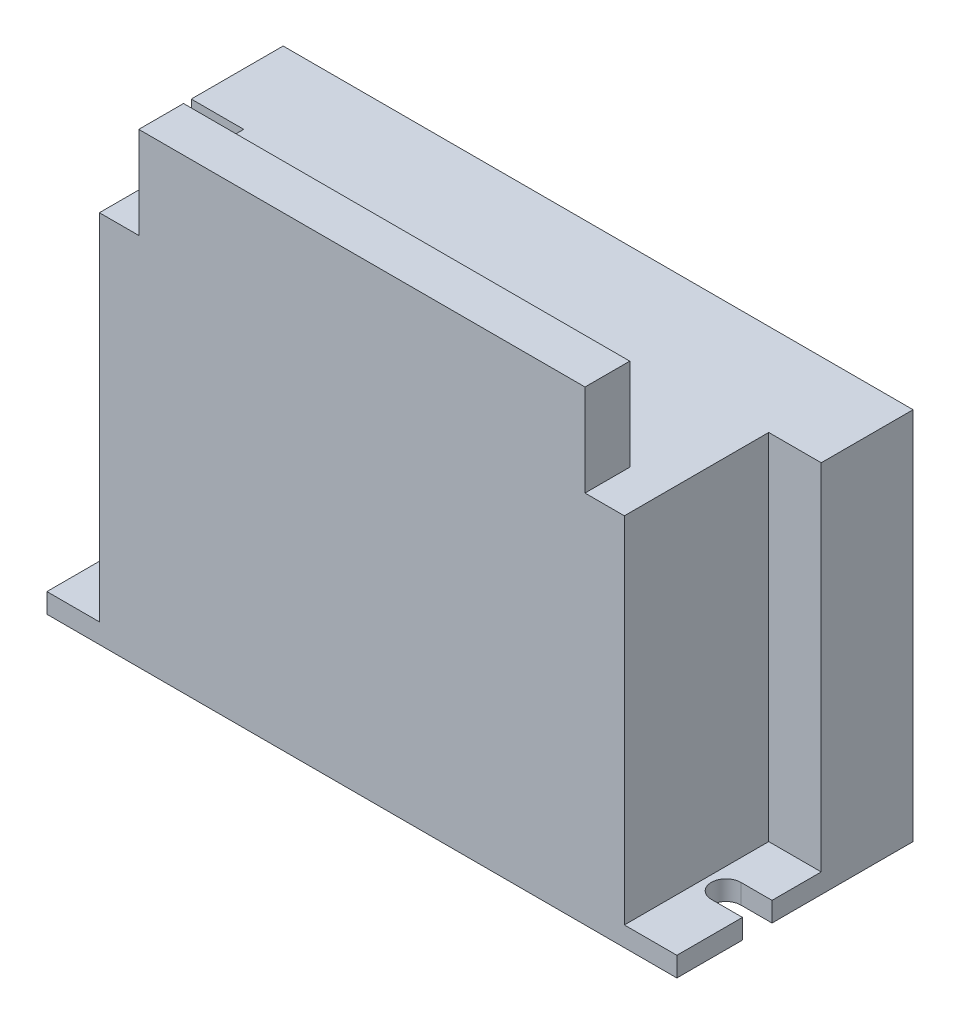
SolidWorks part; units mm, degrees
ref_plane "정면" through (0, 0, 0) normal (0, 0, 1) x (1, 0, 0)
ref_plane "윗면" through (0, 0, 0) normal (0, 1, 0) x (1, 0, 0)
ref_plane "우측면" through (0, 0, 0) normal (1, 0, 0) x (0, 0, -1)
sketch "스케치1" plane through (0, 0, 0) normal (0, 0, 1) x (1, 0, 0)
  line L1 (-48, 28.5) -> (48, 28.5)
  line L2 (-48, 28.5) -> (-48, -28.5)
  line L3 (-48, -28.5) -> (48, -28.5)
  line L4 (48, 28.5) -> (48, -28.5)
  line L5 (-48, 28.5) -> (48, -28.5) construction
  line L6 (-48, -28.5) -> (48, 28.5) construction
  point P0 (0, 0)
  dimension "D1" = 57
  dimension "D2" = 96
extrude "보스-돌출1" add sketch "스케치1" along normal blind 36
sketch "스케치2" plane through (0, 28.5, 0) normal (0, 1, 0) x (1, 0, 0)
  line L1 (-48, -36) -> (-40, -36)
  line L2 (-48, -36) -> (-48, -14)
  line L3 (-48, -14) -> (-40, -14)
  line L4 (-40, -36) -> (-40, -14)
  line L5 (48, -36) -> (40, -36)
  line L6 (48, -36) -> (48, -14)
  line L7 (48, -14) -> (40, -14)
  line L8 (40, -36) -> (40, -14)
  dimension "D1" = 8
  dimension "D2" = 22
  dimension "D3" = 8
  dimension "D4" = 22
extrude "컷-돌출1" cut sketch "스케치2" against normal blind 54
sketch "스케치4" plane through (0, -25.5, 0) normal (0, 1, 0) x (1, 0, 0)
  line L0 (48, -26) -> (43.25, -26)
  line L1 (48, -36) -> (48, -14) construction
  line L2 (48, -26) -> (48, -21.5)
  line L3 (48, -21.5) -> (43.25, -21.5)
  line L4 (40, -36) -> (48, -36) construction
  arc A0 (43.25, -21.5) -> (43.25, -26) centre (43.25, -23.75) ccw
  point P8 (0, 0)
  dimension "D1" = 4.5
  dimension "D2" = 4.75
  dimension "D3" = 12.25
extrude "컷-돌출2" cut sketch "스케치4" against normal blind 54
ref_plane "평면1" through (0, 0, 0) normal (1, 0, 0) x (0, 0, -1)
mirror "대칭 복사1" about plane through (0, 0, 0) normal (1, 0, 0) of "컷-돌출2"
sketch "스케치5" plane through (0, 28.5, 0) normal (0, 1, 0) x (1, 0, 0)
  line L0 (0, -11.825) -> (0, 11.825) construction
  line L1 (-34, -29.1775) -> (34, -29.1775)
  line L2 (-34, -29.1775) -> (-34, -36)
  line L3 (-34, -36) -> (34, -36)
  line L4 (34, -29.1775) -> (34, -36)
  line L5 (-34, -29.1775) -> (34, -36) construction
  line L6 (-34, -36) -> (34, -29.1775) construction
  line L7 (40, -36) -> (-40, -36) construction
  point P0 (0, -32.5888)
  dimension "D1" = 68
  dimension "D2" = 0
  dimension "D3" = 0
extrude "보스-돌출2" add sketch "스케치5" along normal blind 14
